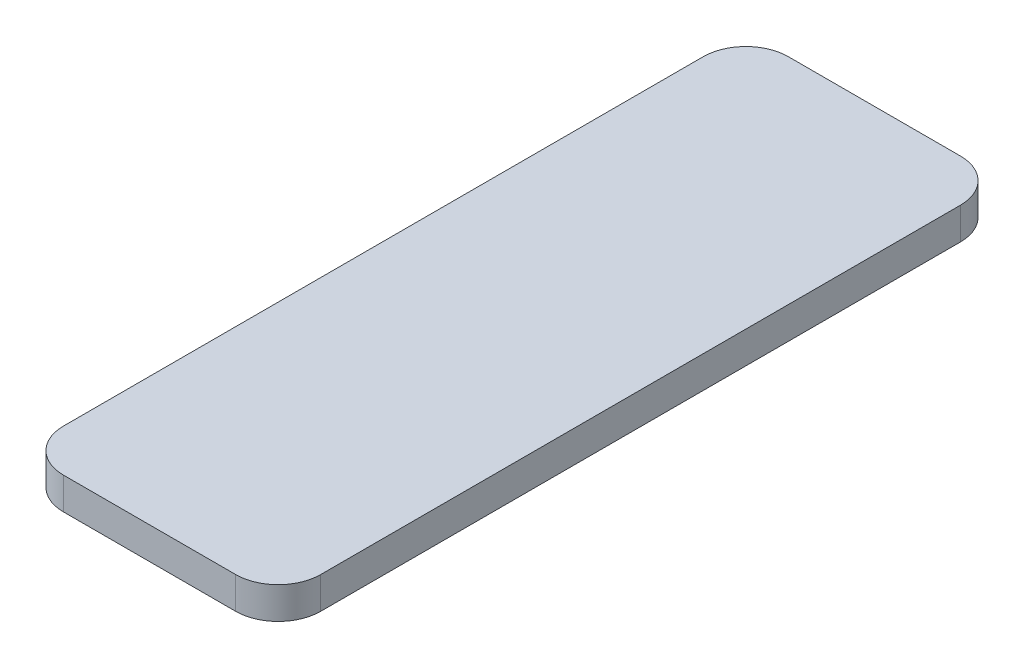
SolidWorks part; units mm, degrees
ref_plane "Front Plane" through (0, 0, 0) normal (0, 0, 1) x (1, 0, 0)
ref_plane "Top Plane" through (0, 0, 0) normal (0, 1, 0) x (1, 0, 0)
ref_plane "Right Plane" through (0, 0, 0) normal (1, 0, 0) x (0, 0, -1)
sketch "Sketch3" plane through (0, 0, 0) normal (0, 0, 1) x (1, 0, 0)
  line L1 (30.25, -3.75) -> (-30.25, -3.75)
  line L2 (30.25, -3.75) -> (30.25, 3.75)
  line L3 (30.25, 3.75) -> (-30.25, 3.75)
  line L4 (-30.25, -3.75) -> (-30.25, 3.75)
  line L5 (30.25, -3.75) -> (-30.25, 3.75) construction
  line L6 (30.25, 3.75) -> (-30.25, -3.75) construction
  point P0 (0, 0)
  dimension "D1" = 60.5
  dimension "D2" = 7.5
extrude "Boss-Extrude1" add sketch "Sketch3" along normal mid plane 170.5
sketch "Sketch4" plane through (0, -3.75, 0) normal (0, -1, 0) x (1, 0, 0)
  line L0 (-30.25, 85.25) -> (-30.25, -85.25) construction
  line L1 (-25.5, -70.25) -> (-27.5, -70.25)
  line L2 (-25.5, -70.25) -> (-25.5, 70.25)
  line L3 (-25.5, 70.25) -> (-27.5, 70.25)
  line L4 (-27.5, -70.25) -> (-27.5, 70.25)
  line L5 (-25.5, -70.25) -> (-27.5, 70.25) construction
  line L6 (-25.5, 70.25) -> (-27.5, -70.25) construction
  line L11 (0, 85.25) -> (0, -85.25) construction
  line L12 (25.5, 70.25) -> (27.5, 70.25)
  line L14 (-30.25, 85.25) -> (30.25, 85.25) construction
  line L15 (-30.25, -85.25) -> (30.25, -85.25) construction
  line L16 (27.5, -70.25) -> (27.5, 70.25)
  line L17 (25.5, -70.25) -> (27.5, -70.25)
  line L18 (25.5, -70.25) -> (25.5, 70.25)
  point P0 (-26.5, 0)
  dimension "D1" = 2.75
  dimension "D2" = 2
  dimension "D3" = 15
  dimension "D5" = 15
extrude "Boss-Extrude2" add sketch "Sketch4" along normal blind 2.5 separate body
fillet "Fillet1" radius 10 4 edges at (-30.25, 0, 85.25) (30.25, 0, 85.25) (30.25, 0, -85.25) (-30.25, 0, -85.25)
